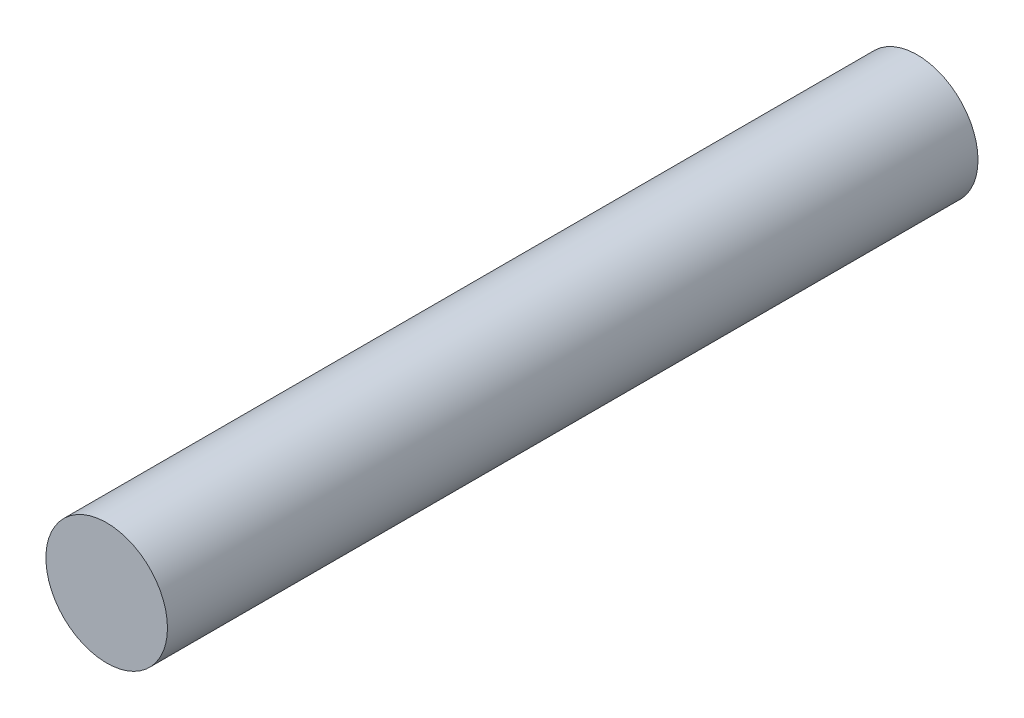
SolidWorks part; units mm, degrees
ref_plane "Front Plane" through (0, 0, 0) normal (0, 0, 1) x (1, 0, 0)
ref_plane "Top Plane" through (0, 0, 0) normal (0, 1, 0) x (1, 0, 0)
ref_plane "Right Plane" through (0, 0, 0) normal (1, 0, 0) x (0, 0, -1)
sketch "Sketch1" plane through (0, 0, 0) normal (0, 0, 1) x (1, 0, 0)
  circle A0 centre (0, 0) radius 0.75
  dimension "D1" = 1.5
extrude "Boss-Extrude1" add sketch "Sketch1" along normal blind 10
